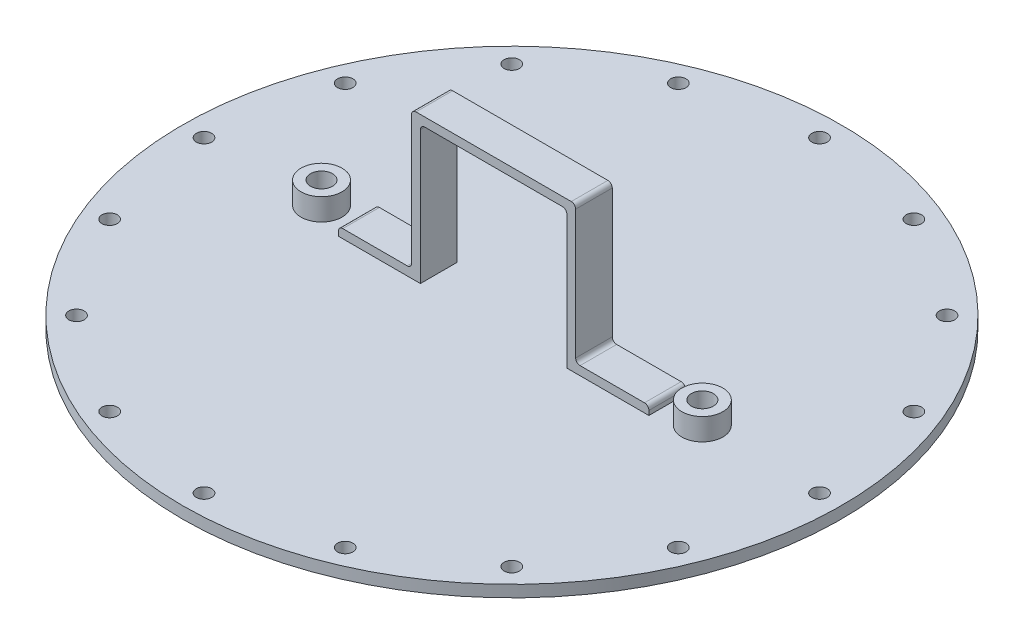
SolidWorks part; units mm, degrees
material "Plain Carbon Steel"
ref_plane "Front Plane" through (0, 0, 0) normal (0, 0, 1) x (1, 0, 0)
ref_plane "Top Plane" through (0, 0, 0) normal (0, 1, 0) x (1, 0, 0)
ref_plane "Right Plane" through (0, 0, 0) normal (1, 0, 0) x (0, 0, -1)
sketch "Sketch1" plane through (0, 0, 0) normal (0, 1, 0) x (1, 0, 0)
  circle A0 centre (0, 0) radius 225
extrude "Boss-Extrude1" add sketch "Sketch1" along normal blind 8
sketch "Sketch2" plane through (0, 8, 0) normal (0, 1, 0) x (1, 0, 0)
  circle A0 centre (0, 210) radius 5.25
extrude "Cut-Extrude1" cut sketch "Sketch2" against normal through all
pattern_circular "CirPattern1" count 16 over 360 about axis through (0, 0, 0.1144) along (0, 1, 0) of "Cut-Extrude1"
sketch "Sketch3" plane through (0, 8, 0) normal (0, 1, 0) x (1, 0, 0)
  circle A0 centre (-130, 0) radius 14
extrude "Boss-Extrude2" add sketch "Sketch3" along normal blind 15
sketch "Sketch4" plane through (0, 23, 0) normal (0, 1, 0) x (1, 0, 0)
  circle A0 centre (-130, 0) radius 7.5
extrude "Cut-Extrude2" cut sketch "Sketch4" against normal through all
sketch "Sketch5" plane through (0, 8, 0) normal (0, 1, 0) x (1, 0, 0)
  circle A0 centre (130, 0) radius 14
extrude "Boss-Extrude3" add sketch "Sketch5" along normal blind 15
sketch "Sketch6" plane through (0, 23, 0) normal (0, 1, 0) x (1, 0, 0)
  circle A0 centre (130, 0) radius 7.5
extrude "Cut-Extrude3" cut sketch "Sketch6" against normal through all
sketch "Sketch7" plane through (0, 0, 0) normal (0, 0, 1) x (1, 0, 0)
  line L0 (-106, 8) -> (-106, 14)
  line L1 (225, 8) -> (-225, 8) construction
  line L2 (-106, 14) -> (-56, 14)
  line L3 (-56, 14) -> (-56, 108)
  line L4 (-56, 108) -> (56, 108)
  line L5 (56, 108) -> (56, 14)
  line L6 (56, 14) -> (106, 14)
  line L7 (106, 14) -> (106, 8)
  line L8 (106, 8) -> (50, 8)
  line L9 (50, 8) -> (50, 102)
  line L10 (50, 102) -> (-50, 102)
  line L11 (-50, 102) -> (-50, 8)
  line L12 (-50, 8) -> (-106, 8)
extrude "Boss-Extrude4" add sketch "Sketch7" along normal mid plane 25
fillet "Fillet1" radius 3 8 edges at (106, 14, 0) (-106, 14, 0) (56, 14, 0) (-56, 14, 0) (50, 102, 0) (-50, 102, 0) (-56, 108, 0) (56, 108, 0)
